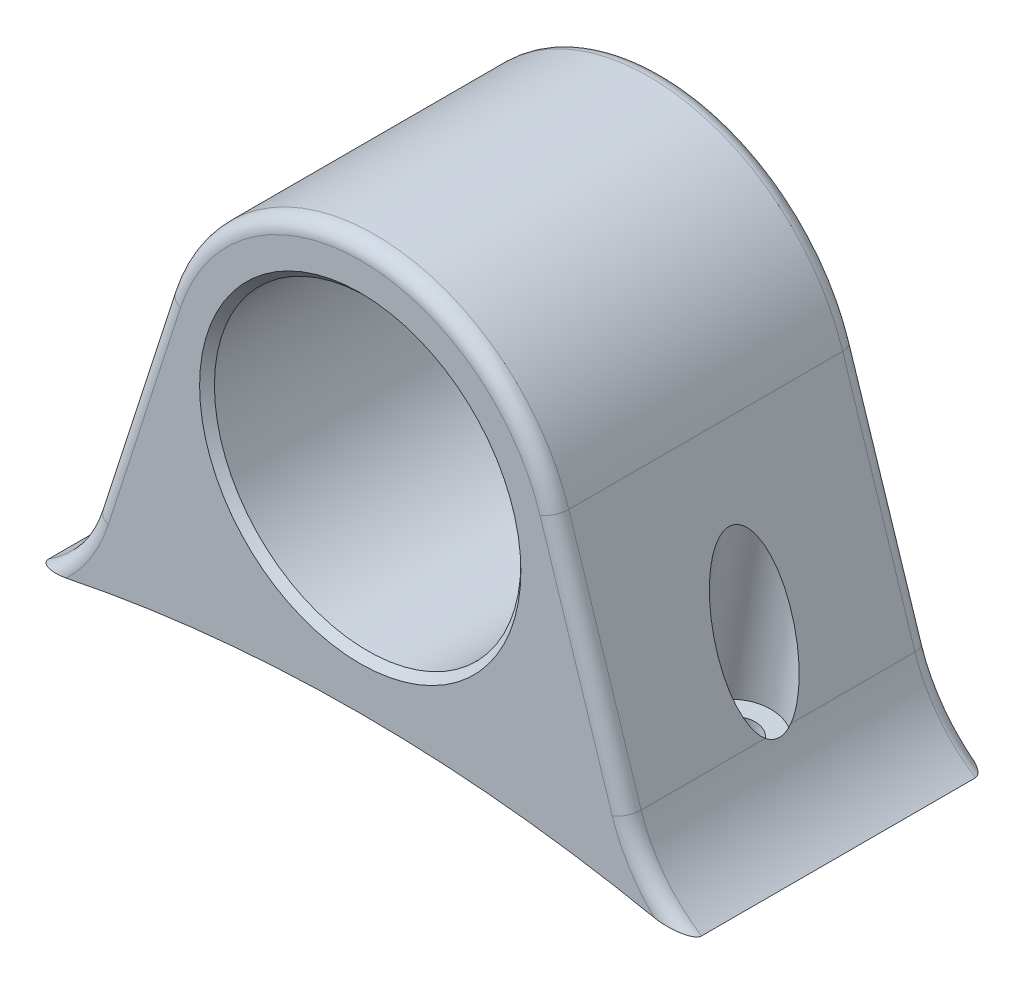
SolidWorks part; units mm, degrees
ref_plane "Front Plane" through (0, 0, 0) normal (0, 0, 1) x (1, 0, 0)
ref_plane "Top Plane" through (0, 0, 0) normal (0, 1, 0) x (1, 0, 0)
ref_plane "Right Plane" through (0, 0, 0) normal (1, 0, 0) x (0, 0, -1)
sketch "Sketch1" plane through (0, 0, 0) normal (0, 0, 1) x (1, 0, 0)
  line L0 (0, 0) -> (0, 76.2) construction
  line L1 (-56.007, 0) -> (56.007, 0) construction
  line L2 (-56.007, 0) -> (-56.007, 69.85) construction
  line L3 (56.007, 0) -> (56.007, 69.85) construction
  line L4 (0, 111.125) -> (0, 76.2) construction
  line L5 (-45.6428, 83.3733) -> (-33.2401, 121.842)
  line L6 (45.6428, 83.3733) -> (33.2401, 121.842)
  line L7 (-56.007, 69.85) -> (-47.6961, 75.2342) construction
  line L8 (-56.007, 69.85) -> (-33.0083, 75.133) construction
  arc A0 (-56.007, 69.85) -> (56.007, 69.85) centre (0, -173.9659) cw
  circle A1 centre (0, 111.125) radius 26.289
  circle A2 centre (0, 111.125) radius 28.702 construction
  arc A3 (33.2401, 121.842) -> (-33.2401, 121.842) centre (0, 111.125) ccw
  arc A4 (-56.007, 69.85) -> (-45.6428, 83.3733) centre (-69.8174, 91.1674) ccw
  arc A5 (56.007, 69.85) -> (45.6428, 83.3733) centre (69.8174, 91.1674) cw
  point P6 (0, 0)
  point P12 (-33.0083, 75.133)
  dimension "D4" = 52.578
  dimension "D5" = 57.404
  dimension "D7" = 34.925
  dimension "D8" = 25.4
  dimension "D1" = 76.2
  dimension "D2" = 112.014
  dimension "D3" = 69.85
  dimension "D6" = 34.925
  dimension "D9" = 20
extrude "Boss-Extrude1" add sketch "Sketch1" against normal blind 48.26
fillet "Fillet1" radius 2.54 5 edges at (49.6572, 75.7167, 0) (39.4414, 102.6076, 0) (-49.6572, 75.7167, 0) (-39.4414, 102.6076, 0) (0, 146.05, 0)
chamfer "Chamfer1" distance 1.27 angle 45 1 edges at (26.289, 111.125, 0)
sketch "Sketch2" plane through (0, 0, -48.26) normal (0, 0, -1) x (-1, 0, 0)
  line L0 (-18.669, 111.125) -> (18.669, 111.125) construction
  line L1 (-21.336, 111.125) -> (-16.002, 111.125) construction
  line L2 (45.6428, 83.3733) -> (33.2401, 121.842)
  line L3 (-33.2401, 121.842) -> (-45.6428, 83.3733)
  line L4 (45.6428, 83.3733) -> (33.2401, 121.842)
  line L5 (-33.2401, 121.842) -> (-45.6428, 83.3733)
  line L6 (-21.336, 113.792) -> (-16.002, 113.792)
  line L7 (-21.336, 108.458) -> (-16.002, 108.458)
  line L8 (0, 111.125) -> (0, 76.2) construction
  line L9 (21.336, 111.125) -> (16.002, 111.125) construction
  line L10 (21.336, 113.792) -> (16.002, 113.792)
  line L11 (21.336, 108.458) -> (16.002, 108.458)
  line L12 (0, 124.333) -> (0, 111.125) construction
  arc A1 (-21.336, 113.792) -> (-21.336, 108.458) centre (-21.336, 111.125) ccw
  arc A2 (-16.002, 108.458) -> (-16.002, 113.792) centre (-16.002, 111.125) ccw
  arc A3 (21.336, 113.792) -> (21.336, 108.458) centre (21.336, 111.125) cw
  arc A4 (-56.007, 69.85) -> (-45.6428, 83.3733) centre (-69.8174, 91.1674) ccw
  arc A5 (56.007, 69.85) -> (-56.007, 69.85) centre (0, -173.9659) ccw
  arc A6 (45.6428, 83.3733) -> (56.007, 69.85) centre (69.8174, 91.1674) ccw
  arc A7 (33.2401, 121.842) -> (-33.2401, 121.842) centre (0, 111.125) ccw
  arc A8 (-56.007, 69.85) -> (-45.6428, 83.3733) centre (-69.8174, 91.1674) ccw
  arc A9 (56.007, 69.85) -> (-56.007, 69.85) centre (0, -173.9659) ccw
  arc A10 (45.6428, 83.3733) -> (56.007, 69.85) centre (69.8174, 91.1674) ccw
  arc A11 (33.2401, 121.842) -> (-33.2401, 121.842) centre (0, 111.125) ccw
  arc A12 (16.002, 108.458) -> (16.002, 113.792) centre (16.002, 111.125) cw
  circle A13 centre (0, 97.917) radius 6.35
  circle A14 centre (0, 124.333) radius 2.54
  point P11 (0, 111.125)
  point P15 (-18.669, 111.125)
  point P23 (18.669, 111.125)
  dimension "D3" = 2.667
  dimension "D6" = 12.7
  dimension "D7" = 5.08
  dimension "D2" = 37.338
  dimension "D4" = 5.334
  dimension "D5" = 13.208
  dimension "D8" = 13.208
  dimension "D1" = 0
extrude "Boss-Extrude2" add sketch "Sketch2" along normal blind 3.81
fillet "Fillet2" radius 2.54 5 edges at (-49.6572, 75.7167, -52.07) (-39.4414, 102.6076, -52.07) (49.6572, 75.7167, -52.07) (39.4414, 102.6076, -52.07) (0, 146.05, -52.07)
ref_plane "Plane1" through (0, 0, -26.035) normal (0, 0, 1) x (-1, 0, 0)
sketch "Sketch3" plane through (0, 0, -26.035) normal (0, 0, 1) x (-1, 0, 0)
  line L0 (0, 173.9659) -> (-41.5582, -96.0422)
  line L1 (-33.2401, -121.842) -> (-45.6428, -83.3733) construction
  line L2 (0, 173.9659) -> (0, 0) construction
  circle A2 centre (0, 173.9659) radius 250.1659 construction
  arc A3 (-50.4092, -71.0686) -> (50.4092, -71.0686) centre (0, 173.9659) ccw construction
  dimension "D1" = 8.75
ref_plane "Plane2" through (11.8998, 77.3143, 0) normal (-0.1521, -0.9884, 0) x (-0.9884, 0.1521, 0)
sketch "Sketch4" plane through (11.8998, 77.3143, 0) normal (-0.1521, -0.9884, 0) x (-0.9884, 0.1521, 0)
  circle A0 centre (-26.4643, 26.035) radius 3.175
  point P0 (-26.4643, 26.035)
  dimension "D1" = 6.35
extrude "Cut-Extrude1" cut sketch "Sketch4" against normal through all both and the other way through all
sketch "Sketch5" plane through (11.8998, 77.3143, 0) normal (-0.1521, -0.9884, 0) x (-0.9884, 0.1521, 0)
  circle A2 centre (-26.4643, 26.035) radius 6.35
  circle A3 centre (-26.4643, 26.035) radius 6.35
  dimension "D1" = 3.175
extrude "Cut-Extrude2" cut sketch "Sketch5" against normal through all from offset 6.35 offset against normal yes
mirror "Mirror1" about plane through (0, 0, 0) normal (1, 0, 0) of "Cut-Extrude2", "Cut-Extrude1"
